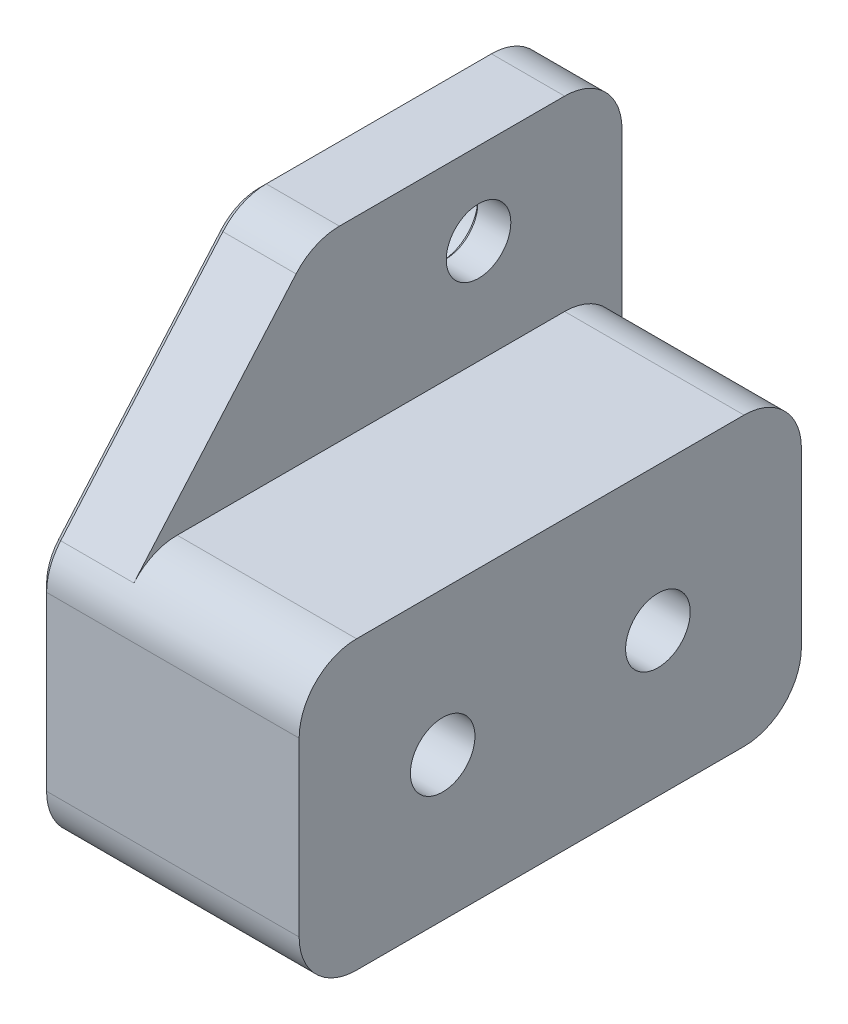
SolidWorks part; units mm, degrees
ref_plane "Front Plane" through (0, 0, 0) normal (0, 0, 1) x (1, 0, 0)
ref_plane "Top Plane" through (0, 0, 0) normal (0, 1, 0) x (1, 0, 0)
ref_plane "Right Plane" through (0, 0, 0) normal (1, 0, 0) x (0, 0, -1)
sketch "Sketch1" plane through (0, 0, 0) normal (1, 0, 0) x (0, 0, -1)
  line L0 (0, -10) -> (0, 23) construction
  line L1 (10, 0) -> (-25, 0) construction
  line L2 (-21, -10) -> (6, -10)
  line L3 (10, -6) -> (10, 19)
  line L4 (6, 23) -> (-9.6957, 23)
  line L5 (-12.7141, 21.6247) -> (-24.0184, 8.6247)
  line L6 (-25, 6) -> (-25, -6)
  line L7 (0, 17.25) -> (-15, 0) construction
  circle A0 centre (0, 0) radius 2 construction
  circle A1 centre (0, 17.25) radius 2 construction
  circle A2 centre (-15, 0) radius 2.25
  circle A3 centre (0, 17.25) radius 2.25
  circle A4 centre (0, 0) radius 2.25
  arc A5 (6, -10) -> (10, -6) centre (6, -6) ccw
  arc A6 (10, 19) -> (6, 23) centre (6, 19) ccw
  arc A7 (-9.6957, 23) -> (-12.7141, 21.6247) centre (-9.6957, 19) ccw
  arc A8 (-24.0184, 8.6247) -> (-25, 6) centre (-21, 6) ccw
  arc A9 (-25, -6) -> (-21, -10) centre (-21, -6) ccw
  point P30 (-25, 0)
  dimension "D2" = 4
  dimension "D3" = 4
  dimension "D10" = 4
  dimension "D5" = 15
  dimension "D6" = 17.25
  dimension "D7" = 10
  dimension "D8" = 10
  dimension "D9" = 5.75
  dimension "D11" = 10
  dimension "D1" = 0.25
  dimension "D4" = 0.25
extrude "Boss-Extrude1" add sketch "Sketch1" along normal blind 2.6
sketch "Sketch3" plane through (0, 0, 0) normal (1, 0, 0) x (0, 0, -1)
  line L5 (-21, -10) -> (6, -10)
  line L6 (10, -6) -> (10, 19)
  line L7 (6, 23) -> (-9.6957, 23)
  line L8 (-12.7141, 21.6247) -> (-24.0184, 8.6247)
  line L9 (-25, 6) -> (-25, -6)
  line L10 (-21, -10) -> (6, -10)
  line L11 (10, -6) -> (10, 19)
  line L12 (6, 23) -> (-9.6957, 23)
  line L13 (-12.7141, 21.6247) -> (-24.0184, 8.6247)
  line L14 (-25, 6) -> (-25, -6)
  circle A0 centre (0, 0) radius 3.5 construction
  circle A1 centre (-15, 0) radius 3.75
  circle A2 centre (-15, 0) radius 2.25 construction
  circle A3 centre (0, 0) radius 2.25 construction
  circle A4 centre (0, 0) radius 3.75
  arc A5 (-25, -6) -> (-21, -10) centre (-21, -6) ccw
  arc A6 (6, -10) -> (10, -6) centre (6, -6) ccw
  arc A7 (10, 19) -> (6, 23) centre (6, 19) ccw
  arc A8 (-9.6957, 23) -> (-12.7141, 21.6247) centre (-9.6957, 19) ccw
  arc A9 (-24.0184, 8.6247) -> (-25, 6) centre (-21, 6) ccw
  arc A10 (-25, -6) -> (-21, -10) centre (-21, -6) ccw
  arc A11 (6, -10) -> (10, -6) centre (6, -6) ccw
  arc A12 (10, 19) -> (6, 23) centre (6, 19) ccw
  arc A13 (-9.6957, 23) -> (-12.7141, 21.6247) centre (-9.6957, 19) ccw
  arc A14 (-24.0184, 8.6247) -> (-25, 6) centre (-21, 6) ccw
  circle A15 centre (0, 17.25) radius 3.75
  circle A16 centre (0, 17.25) radius 2.25 construction
  dimension "D2" = 7
  dimension "D3" = 0.25
extrude "Boss-Extrude3" add sketch "Sketch3" against normal blind 3
chamfer "Chamfer2" distance 0.3 angle 45 6 edges at (0, 0, 11.25) (0, 0, 12.75) (0, 0, -3.75) (0, 0, -2.25) (0, 17.25, -2.25) (0, 17.25, -3.75)
chamfer "Chamfer3" distance 0.5 angle 45 13 edges at (-3, 0, -3.75) (-3, 0, 25) (-3, 7.4011, 24.7466) (-3, 15.1247, 18.3662) (-3, 22.64, 11.3541) (-3, 23, 1.8478) (-3, 21.8284, -8.8284) (-3, 6.5, -10) (-3, -8.8284, -8.8284) (-3, -10, 7.5) (-3, -8.8284, 23.8284) (-3, 0, 11.25) (-3, 17.25, -3.75)
sketch "Sketch4" plane through (2.6, 0, 0) normal (1, 0, 0) x (0, 0, -1)
  line L0 (-21, -10) -> (6, -10) construction
  line L1 (-21, -10) -> (6, -10)
  line L2 (-25, 0) -> (10, 0) construction
  line L3 (-25, 6) -> (-25, -6) construction
  line L4 (10, -6) -> (10, 19) construction
  line L5 (-25, -6) -> (-25, 6)
  line L6 (10, -6) -> (10, 6)
  line L7 (-21, 10) -> (6, 10)
  circle A0 centre (0, 0) radius 2.25 construction
  circle A1 centre (-15, 0) radius 2.25 construction
  arc A2 (6, -10) -> (10, -6) centre (6, -6) ccw construction
  arc A3 (-25, -6) -> (-21, -10) centre (-21, -6) ccw construction
  circle A4 centre (0, 0) radius 2.25
  circle A5 centre (-15, 0) radius 2.25
  arc A6 (6, -10) -> (10, -6) centre (6, -6) ccw
  arc A7 (-25, -6) -> (-21, -10) centre (-21, -6) ccw
  arc A8 (-25, 6) -> (-21, 10) centre (-21, 6) cw
  arc A9 (10, 6) -> (6, 10) centre (6, 6) ccw
  point P19 (10, 0)
  point P23 (-25, 0)
extrude "Boss-Extrude4" add sketch "Sketch4" along normal blind 12.5
equation "\"Tolerance\" = 0.25mm"
equation "\"D1@Sketch1\"=\"Tolerance\""
equation "\"D4@Sketch1\"=\"Tolerance\""
equation "\"Pocket_Head_M5\"= 8mm"
equation "\"Pocket_Head_M4\" = 7mm"
equation "\"D2@Sketch3\"=\"Pocket_Head_M4\""
equation "\"D3@Sketch3\"=\"Tolerance\""
equation "\"Pocket_Nut_M4\" = 7mm"
